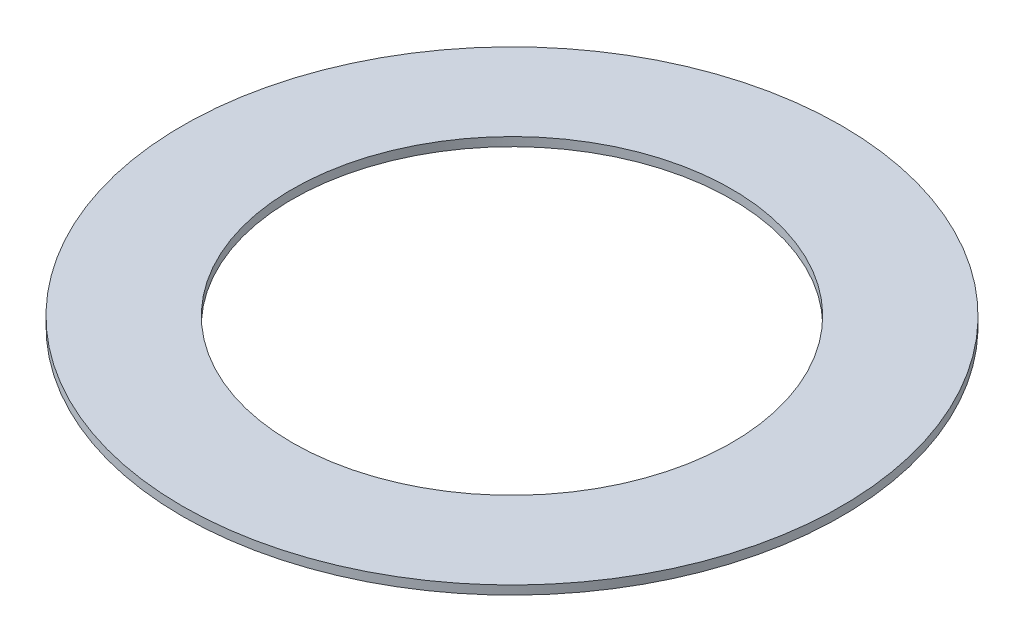
SolidWorks part; units mm, degrees
material "AISI 316 Annealed Stainless Steel Bar (SS)"
ref_plane "Front" through (0, 0, 0) normal (0, 0, 1) x (1, 0, 0)
ref_plane "Top" through (0, 0, 0) normal (0, 1, 0) x (1, 0, 0)
ref_plane "Right" through (0, 0, 0) normal (1, 0, 0) x (0, 0, -1)
sketch "Sketch1" plane through (0, 0, 0) normal (0, 1, 0) x (1, 0, 0)
  circle A0 centre (0, 0) radius 3.175
  circle A1 centre (0, 0) radius 4.7625
  dimension "D1" = 9.525
  dimension "D2" = 6.35
extrude "Boss-Extrude1" add sketch "Sketch1" along normal blind 0.127
